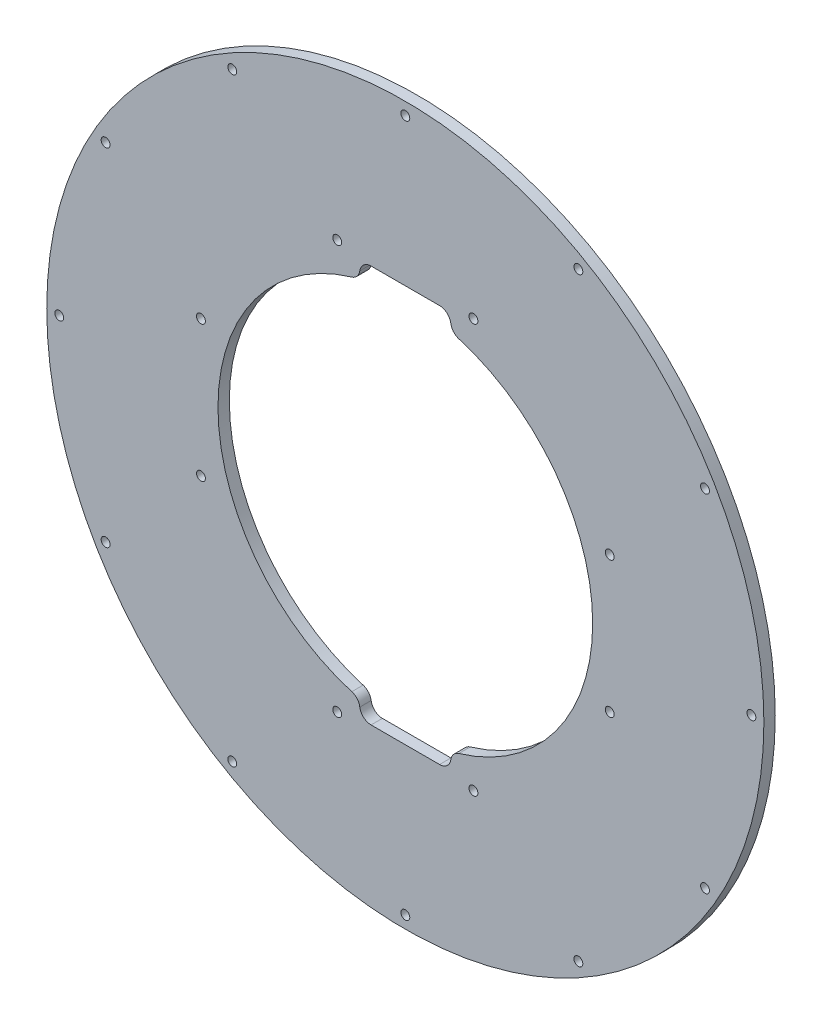
SolidWorks part; units mm, degrees
ref_plane "Front Plane" through (0, 0, 0) normal (1, 0, 0) x (0, 1, 0)
ref_plane "Top Plane" through (0, 0, 0) normal (0, 0, 1) x (0, 1, 0)
ref_plane "Right Plane" through (0, 0, 0) normal (0, 1, 0) x (-1, 0, 0)
sketch "Sketch1" plane through (0, 0, 0) normal (0, 0, 1) x (0, 1, 0)
  circle A0 centre (0, 0) radius 104.775
  circle A1 centre (0, 0) radius 200.533
  circle A2 centre (0, 0) radius 193.548 construction
  point P5 (-167.6175, 96.774)
  point P9 (-96.774, 167.6175)
  point P10 (0, 193.548)
  point P11 (96.774, 167.6175)
  point P12 (167.6175, 96.774)
  point P13 (193.548, 0)
  point P14 (167.6175, -96.774)
  point P15 (96.774, -167.6175)
  point P16 (0, -193.548)
  point P17 (-96.774, -167.6175)
  point P18 (-167.6175, -96.774)
  point P19 (-193.548, 0)
  point P20 (0, 0)
  dimension "D1" = 209.55
  dimension "D2" = 401.066
  dimension "D3" = 387.096
  dimension "D4" = 12
extrude "Boss-Extrude1" add sketch "Sketch1" along normal blind 6.35
sketch "Sketch2" plane through (0, 0, 6.35) normal (0, 0, 1) x (1, 0, 0)
  point P0 (-96.774, 167.6175)
  point P2 (-167.6175, 96.774)
  point P4 (-193.548, 0)
  point P6 (-167.6175, -96.774)
  point P8 (-96.774, -167.6175)
  point P10 (0, -193.548)
  point P12 (96.774, -167.6175)
  point P14 (167.6175, -96.774)
  point P16 (193.548, 0)
  point P18 (167.6175, 96.774)
  point P20 (96.774, 167.6175)
  point P22 (0, 193.548)
hole_wizard "#9 (0.196) Diameter Hole1" positions "Sketch2" profile "Sketch3" hole size "#9" standard "ANSI Inch" end condition through all
sketch "Sketch3" plane through (-96.774, 167.6175, 6.35) normal (1, 0, 0) x (0, -1, 0)
  line L0 (0, 0) -> (0, 6.35)
  line L1 (0, 6.35) -> (2.4892, 6.35)
  line L2 (2.4892, 6.35) -> (2.4892, 0)
  line L5 (2.4892, 0) -> (0, 0)
  line L11 (0, -6.35) -> (0, 107.95) construction
  dimension "Thru Hole Dia." = 4.9784
  dimension "Thru Hole Depth" = 6.35
sketch "Sketch4" plane through (0, 0, 6.35) normal (0, 0, 1) x (1, 0, 0)
  line L0 (0, 0) -> (0, 88.9) construction
  line L1 (-25.4, 76.2) -> (25.4, 76.2) construction
  line L2 (-25.4, 76.2) -> (-25.4, 101.6) construction
  line L3 (-25.4, 101.6) -> (25.4, 101.6) construction
  line L4 (25.4, 76.2) -> (25.4, 101.6) construction
  line L5 (-25.4, 76.2) -> (25.4, 101.6) construction
  line L6 (-25.4, 101.6) -> (25.4, 76.2) construction
  line L8 (-25.4, 101.6) -> (25.4, 101.6)
  line L9 (-25.4, 101.6) -> (-25.4, 111.125)
  line L10 (-25.4, 111.125) -> (25.4, 111.125)
  line L11 (25.4, 101.6) -> (25.4, 111.125)
  line L12 (-25.4, 101.6) -> (25.4, 111.125) construction
  line L13 (-25.4, 111.125) -> (25.4, 101.6) construction
  line L14 (-25.4, -101.6) -> (-25.4, -111.125)
  line L15 (25.4, -111.125) -> (-25.4, -111.125)
  line L16 (25.4, -101.6) -> (25.4, -111.125)
  line L17 (25.4, -101.6) -> (-25.4, -101.6)
  point P0 (0, 88.9)
  point P5 (-38.1, 114.3)
  point P6 (38.1, 114.3)
  point P7 (0, 106.3625)
  point P10 (114.3, 38.1)
  point P11 (114.3, -38.1)
  point P12 (38.1, -114.3)
  point P13 (-38.1, -114.3)
  point P14 (-114.3, -38.1)
  point P15 (-114.3, 38.1)
  dimension "D1" = 76.2
  dimension "D2" = 50.8
  dimension "D3" = 25.4
  dimension "D4" = 12.7
  dimension "D5" = 12.7
  dimension "D6" = 12.7
  dimension "D8" = 50.8
  dimension "D9" = 9.525
  dimension "D7" = 4
  dimension "D10" = 2
extrude "Cut-Extrude1" cut sketch "Sketch4" against normal through all
sketch "Sketch6" plane through (0, 0, 6.35) normal (0, 0, 1) x (1, 0, 0)
  point P0 (-114.3, 38.1)
  point P2 (-114.3, -38.1)
  point P4 (-38.1, -114.3)
  point P6 (38.1, -114.3)
  point P8 (114.3, -38.1)
  point P10 (114.3, 38.1)
  point P12 (38.1, 114.3)
  point P14 (-38.1, 114.3)
hole_wizard "#9 (0.196) Diameter Hole2" positions "Sketch6" profile "Sketch7" hole size "#9" standard "ANSI Inch" end condition through all
sketch "Sketch7" plane through (-114.3, 38.1, 6.35) normal (1, 0, 0) x (0, -1, 0)
  line L0 (0, 0) -> (0, 6.35)
  line L1 (0, 6.35) -> (2.4892, 6.35)
  line L2 (2.4892, 6.35) -> (2.4892, 0)
  line L5 (2.4892, 0) -> (0, 0)
  line L11 (0, -6.35) -> (0, 107.95) construction
  dimension "Thru Hole Dia." = 4.9784
  dimension "Thru Hole Depth" = 6.35
fillet "Fillet1" radius 6.35 4 edges at (-25.4, -101.6496, 3.175) (25.4, -101.6496, 3.175) (25.4, 101.6496, 3.175) (-25.4, 101.6496, 3.175)
fillet "Fillet2" radius 6.35 4 edges at (25.4, -111.125, 3.175) (-25.4, -111.125, 3.175) (25.4, 111.125, 3.175) (-25.4, 111.125, 3.175)
